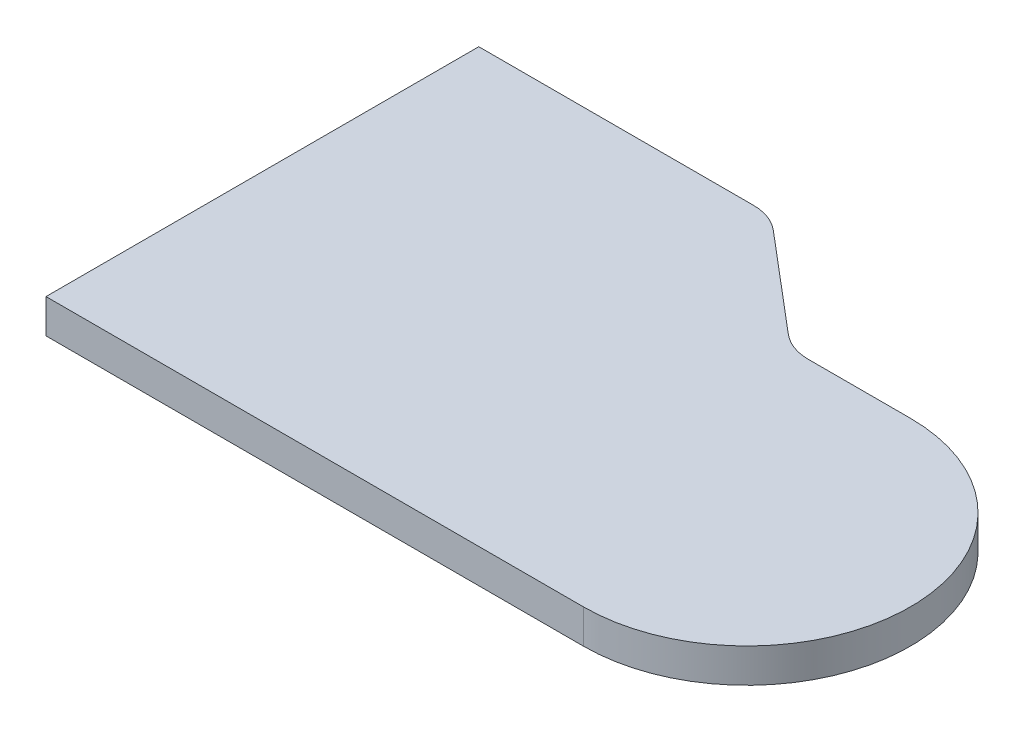
SolidWorks part; units mm, degrees
ref_plane "Front Plane" through (0, 0, 0) normal (0, 0, 1) x (1, 0, 0)
ref_plane "Top Plane" through (0, 0, 0) normal (0, 1, 0) x (1, 0, 0)
ref_plane "Right Plane" through (0, 0, 0) normal (1, 0, 0) x (0, 0, -1)
sketch "Sketch1" plane through (0, 0, 0) normal (0, 1, 0) x (1, 0, 0)
  line L1 (0, 0) -> (70.1287, 0)
  line L2 (0, 0) -> (0, 56.4618)
  line L3 (56.8098, 42.6378) -> (70.1287, 42.6378)
  line L6 (52.7081, 44.1403) -> (39.9219, 54.9593)
  line L7 (35.8202, 56.4618) -> (0, 56.4618)
  arc A0 (70.1287, 0) -> (70.1287, 42.6378) centre (70.1287, 21.3189) ccw
  arc A1 (52.7081, 44.1403) -> (56.8098, 42.6378) centre (56.8098, 48.9878) ccw
  arc A2 (39.9219, 54.9593) -> (35.8202, 56.4618) centre (35.8202, 50.1118) ccw
  dimension "D1" = 6.35
sketch "Sketch2" plane through (0, 0, 0) normal (1, 0, 0) x (0, 0, -1)
  line L0 (0, 2.6108) -> (0, 1.66)
  line L1 (-3.9786, 2.8648) -> (-0.254, 2.8648)
  line L2 (-3.9786, 2.8648) -> (-3.9786, -0.0041)
  line L3 (-3.9786, -0.0041) -> (4.4961, -0.0041)
  line L4 (4.4961, 0.644) -> (4.4961, -0.0041)
  line L5 (0.508, 1.152) -> (3.9881, 1.152)
  arc A0 (0, 1.66) -> (0.508, 1.152) centre (0.508, 1.66) ccw
  arc A1 (-0.254, 2.8648) -> (0, 2.6108) centre (-0.254, 2.6108) cw
  arc A2 (4.4961, 0.644) -> (3.9881, 1.152) centre (3.9881, 0.644) ccw
  point P0 (0, 0)
  dimension "D1" = 0.508
  dimension "D2" = 0.254
  dimension "D3" = 0.508
extrude "Extrude2" add sketch "Sketch1" against normal blind 4.445
